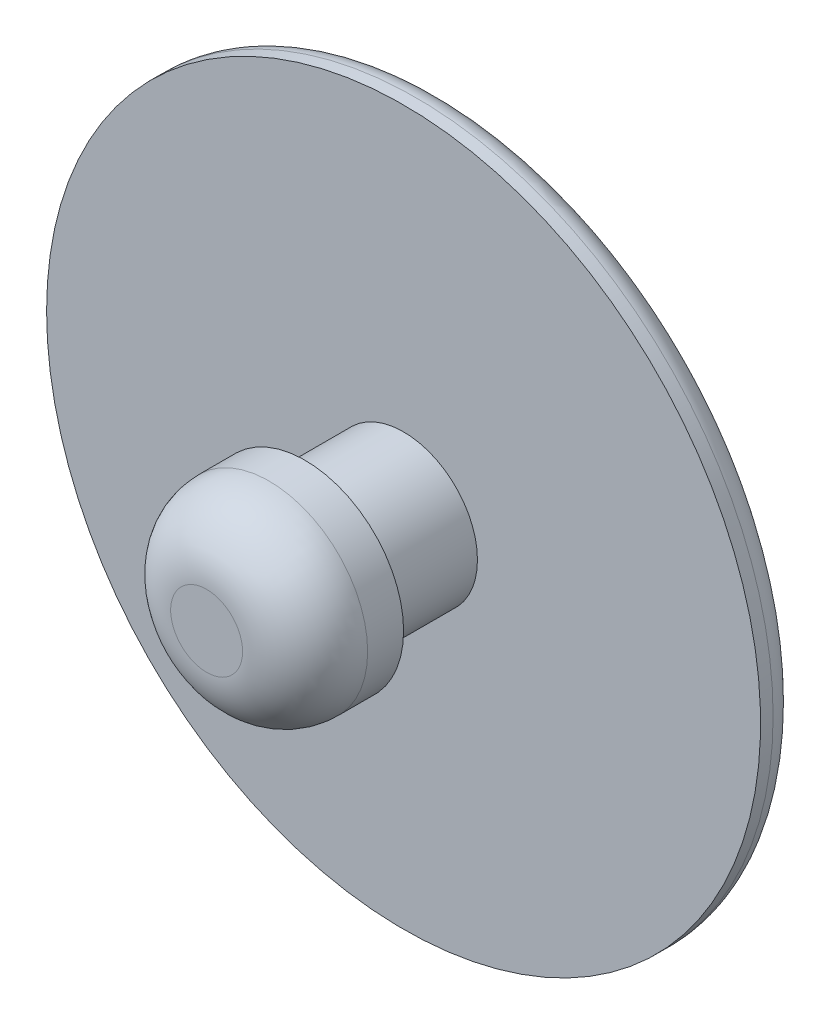
SolidWorks part; units mm, degrees
ref_plane "Front Plane" through (0, 0, 0) normal (0, 0, 1) x (1, 0, 0)
ref_plane "Top Plane" through (0, 0, 0) normal (0, 1, 0) x (1, 0, 0)
ref_plane "Right Plane" through (0, 0, 0) normal (1, 0, 0) x (0, 0, -1)
sketch "Sketch1" plane through (0, 0, 0) normal (0, 0, 1) x (1, 0, 0)
  circle A0 centre (0, 0) radius 7.25
  dimension "D1" = 14.5
extrude "Boss-Extrude1" add sketch "Sketch1" along normal blind 0.762
fillet "Fillet1" radius 0.508 1 edges at (7.25, 0, 0)
sketch "Sketch2" plane through (0, 0, 0.762) normal (0, 0, 1) x (1, 0, 0)
  circle A0 centre (0, 0) radius 1.5
  dimension "D1" = 3
extrude "Boss-Extrude2" add sketch "Sketch2" along normal blind 2
sketch "Sketch3" plane through (0, 0, 2.762) normal (0, 0, 1) x (1, 0, 0)
  circle A0 centre (0, 0) radius 2
  dimension "D1" = 4
extrude "Boss-Extrude3" add sketch "Sketch3" along normal blind 2
fillet "Fillet2" radius 1.27 1 edges at (2, 0, 4.762)
